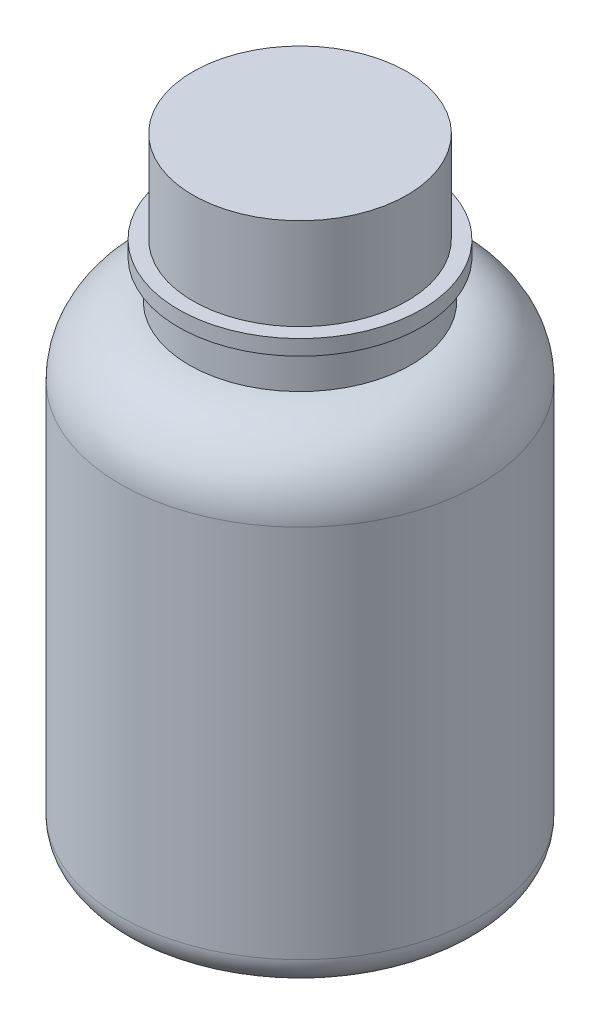
SolidWorks part; units mm, degrees
ref_plane "前视基准面" through (0, 0, 0) normal (0, 0, 1) x (1, 0, 0)
ref_plane "上视基准面" through (0, 0, 0) normal (0, 1, 0) x (1, 0, 0)
ref_plane "右视基准面" through (0, 0, 0) normal (1, 0, 0) x (0, 0, -1)
other "Configuration Table"
sketch "草图1" plane through (0, 0, 0) normal (0, 0, 1) x (1, 0, 0)
  line L0 (0, -4.7776) -> (0, 4.7776) construction
  line L1 (-15.909, 44) -> (-14, 44) construction
  line L2 (-19.5, -25) -> (19.5, -25)
  line L3 (-23.5, -21) -> (-23.5, 25)
  line L5 (23.5, -21) -> (23.5, 25)
  line L6 (-23.5, -25) -> (23.5, 25) construction
  line L7 (-23.5, 25) -> (23.5, -25) construction
  line L9 (-14, 44) -> (-14, 56)
  line L10 (-14, 56) -> (14, 56)
  line L11 (14, 44) -> (14, 56)
  line L12 (-14, 44) -> (14, 56) construction
  line L13 (-14, 56) -> (14, 44) construction
  line L16 (15.909, 44) -> (14, 44)
  line L17 (15.909, 44) -> (15.909, 42)
  line L18 (15.909, 42) -> (14.5, 42)
  line L19 (-15.909, 44) -> (-15.909, 42)
  line L20 (0, 0) -> (0, 73.7116) construction
  line L23 (-14.5, 42) -> (-14.5, 37)
  line L25 (14.5, 42) -> (14.5, 37)
  line L26 (23.5, 28) -> (23.5, 25)
  line L28 (-23.5, 28) -> (-23.5, 25)
  line L29 (-14.5, 42) -> (-15.909, 42)
  line L30 (-14, 44) -> (-15.909, 44)
  line L31 (14, 44) -> (15.909, 44) construction
  line L32 (0, 60.4044) -> (0, -40.3542)
  arc A2 (-19.5, -25) -> (-23.5, -21) centre (-19.5, -21) cw
  arc A3 (19.5, -25) -> (23.5, -21) centre (19.5, -21) ccw
  arc A4 (-14.5, 37) -> (-23.5, 28) centre (-14.5, 28) ccw
  arc A5 (14.5, 37) -> (23.5, 28) centre (14.5, 28) cw
  point P0 (0, 0)
  point P4 (0, 0)
  point P10 (0, 50)
  point P17 (0, 44)
  dimension "D8" = 4
  dimension "D11" = 9
  dimension "D1" = 47
  dimension "D2" = 50
  dimension "D3" = 81
  dimension "D4" = 28
  dimension "D5" = 12
  dimension "D6" = 2
  dimension "D7" = 0
revolve "旋转1" add sketch "草图1" angle 360 about L20
